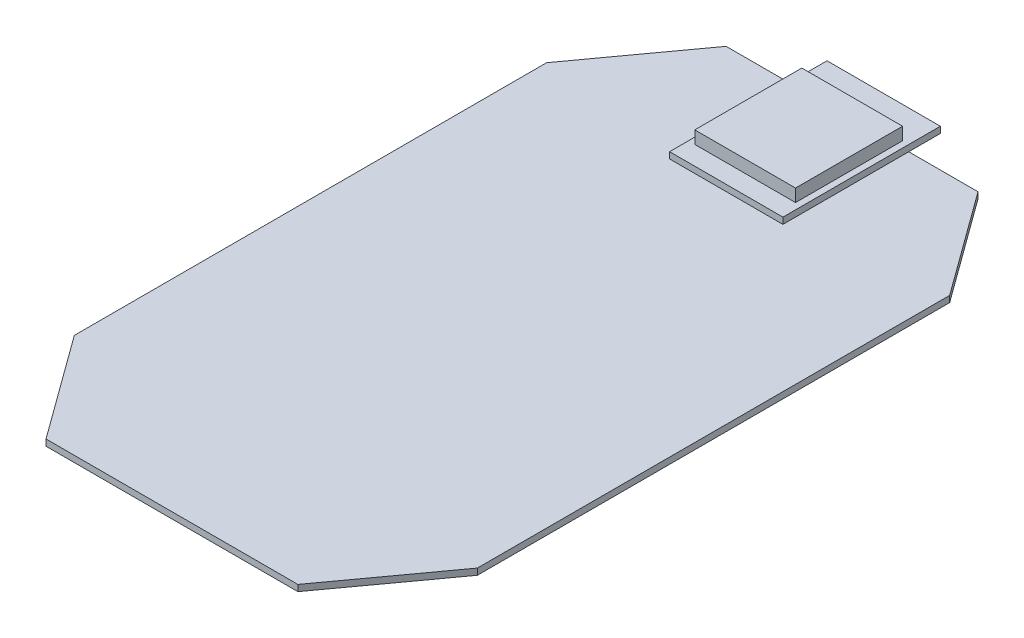
SolidWorks part; units mm, degrees
ref_plane "Front Plane" through (0, 0, 0) normal (0, 0, 1) x (1, 0, 0)
ref_plane "Top Plane" through (0, 0, 0) normal (0, 1, 0) x (1, 0, 0)
ref_plane "Right Plane" through (0, 0, 0) normal (1, 0, 0) x (0, 0, -1)
sketch "Sketch1" plane through (0, 0, 0) normal (0, 1, 0) x (1, 0, 0)
  line L0 (0, 0) -> (40, 0)
  line L1 (20, 0) -> (20, 108)
  line L2 (20, 108) -> (40, 108)
  line L3 (20, 108) -> (0, 108)
  line L4 (20, 54) -> (52, 54)
  line L5 (20, 54) -> (-12, 54)
  line L6 (52, 54) -> (52, 91.5)
  line L7 (52, 54) -> (52, 16.5)
  line L8 (52, 91.5) -> (40, 108)
  line L9 (52, 16.5) -> (40, 0)
  line L10 (-12, 54) -> (-12, 91.5)
  line L11 (-12, 91.5) -> (0, 108)
  line L12 (-12, 54) -> (-12, 16.5)
  line L13 (-12, 16.5) -> (0, 0)
  line L14 (20, 108) -> (29, 108)
  line L15 (20, 108) -> (11, 108)
  line L16 (11, 108) -> (11, 113.0236)
  line L17 (11, 113.0236) -> (29, 113.0236)
  line L18 (29, 113.0236) -> (29, 108)
  dimension "D1" = 40
  dimension "D2" = 108
  dimension "D3" = 20
  dimension "D4" = 20
  dimension "D5" = 32
  dimension "D6" = 32
  dimension "D7" = 37.5
  dimension "D8" = 37.5
  dimension "D9" = 9
  dimension "D10" = 9
  dimension "D11" = 5.0236
extrude "Boss-Extrude3" add sketch "Sketch1" along normal blind 1 contours L11 L10 L5 L1 L3 | L6 L8 L2 L1 L4 | L12 L13 L0 L1 L5 | L9 L7 L4 L1 L0 | L18 L17 L16 L3 L2
sketch "Sketch5" plane through (0, 1, 0) normal (0, 1, 0) x (1, 0, 0)
  line L0 (20, 113.0236) -> (20, 108.0236)
  line L1 (11, 113.0236) -> (29, 113.0236) construction
  line L2 (20, 108.0236) -> (20, 91.0236)
  line L3 (20, 91.0236) -> (28, 91.0236)
  line L4 (20, 91.0236) -> (12, 91.0236)
  line L5 (12, 91.0236) -> (12, 108.0236)
  line L6 (12, 108.0236) -> (28, 108.0236)
  line L7 (28, 108.0236) -> (28, 91.0236)
  dimension "D1" = 17
  dimension "D2" = 5
  dimension "D3" = 8
  dimension "D4" = 8
extrude "Boss-Extrude4" add sketch "Sketch5" along normal blind 3 contours L6 L5 L4 L2 | L7 L6 L2 L3
sketch "Sketch6" plane through (0, 1, 0) normal (0, 1, 0) x (1, 0, 0)
  line L0 (11, 113.0236) -> (29, 113.0236)
  line L1 (29, 113.0236) -> (29, 88.0236)
  line L2 (29, 88.0236) -> (11, 88.0236)
  line L3 (11, 88.0236) -> (11, 113.0236)
  line L4 (28, 108.0236) -> (12, 108.0236)
  line L5 (12, 108.0236) -> (28, 108.0236) construction
  line L6 (12, 108.0236) -> (28, 108.0236) construction
  line L7 (12, 108.0236) -> (12, 91.0236)
  line L8 (12, 91.0236) -> (28, 91.0236)
  line L9 (28, 91.0236) -> (28, 108.0236)
  dimension "D1" = 25
extrude "Boss-Extrude5" add sketch "Sketch6" along normal blind 1 contours L3 L0 L1 L2
sketch "Sketch7" plane through (0, 0, 0) normal (0, -1, 0) x (1, 0, 0)
  line L0 (11, -108) -> (29, -108)
  line L1 (29, -108) -> (29, -113.0236)
  line L2 (29, -113.0236) -> (11, -113.0236)
  line L3 (11, -113.0236) -> (11, -108)
extrude "Cut-Extrude4" cut sketch "Sketch7" against normal blind 1
ref_plane "Plane6" through (0, 1, -108) normal (-1, 0, 0) x (0, 0, 1)
